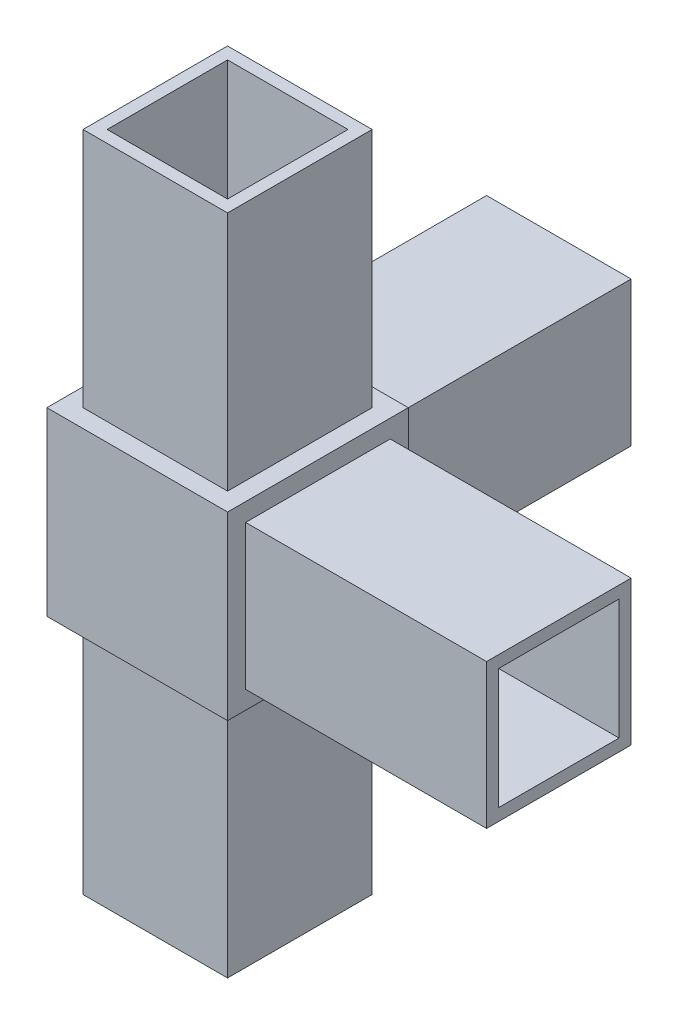
SolidWorks part; units mm, degrees
ref_plane "Alzado" through (0, 0, 0) normal (0, 0, 1) x (1, 0, 0)
ref_plane "Planta" through (0, 0, 0) normal (0, 1, 0) x (1, 0, 0)
ref_plane "Vista lateral" through (0, 0, 0) normal (1, 0, 0) x (0, 0, -1)
sketch "Croquis1" plane through (0, 0, 0) normal (0, 1, 0) x (1, 0, 0)
  line L1 (15, -15) -> (-15, -15)
  line L2 (15, -15) -> (15, 15)
  line L3 (15, 15) -> (-15, 15)
  line L4 (-15, -15) -> (-15, 15)
  line L5 (15, -15) -> (-15, 15) construction
  line L6 (15, 15) -> (-15, -15) construction
  line L7 (15, -15) -> (55, -15)
  line L8 (15, -15) -> (15, 15)
  line L9 (15, 15) -> (55, 15)
  line L10 (55, -15) -> (55, 15)
  line L11 (-15, 15) -> (15, 15)
  line L12 (-15, 15) -> (-15, 55)
  line L13 (-15, 55) -> (15, 55)
  line L14 (15, 15) -> (15, 55)
  point P0 (0, 0)
  dimension "D1" = 30
  dimension "D2" = 30
  dimension "D3" = 40
  dimension "D4" = 40
extrude "Extruir1" add sketch "Croquis1" along normal blind 30 contours L3 L14 L13 L12 | L4 L1 L2 L3 | L7 L10 L9 L2
sketch "Croquis5" plane through (0, 0, 0) normal (0, -1, 0) x (1, 0, 0)
  line L1 (-15, 15) -> (15, 15)
  line L2 (-15, 15) -> (-15, -15)
  line L3 (-15, -15) -> (15, -15)
  line L4 (15, 15) -> (15, -15)
extrude "Extruir4" add sketch "Croquis5" along normal blind 40
sketch "Croquis8" plane through (0, 30, 0) normal (0, 1, 0) x (1, 0, 0)
  line L1 (-15, -15) -> (15, -15)
  line L2 (-15, -15) -> (-15, 15)
  line L3 (-15, 15) -> (15, 15)
  line L4 (15, -15) -> (15, 15)
extrude "Extruir6" add sketch "Croquis8" along normal blind 40
sketch "Croquis9" plane through (0, 70, 0) normal (0, 1, 0) x (1, 0, 0)
  line L0 (-12, 12) -> (-12, -12)
  line L1 (-12, -12) -> (12, -12)
  line L2 (12, -12) -> (12, 12)
  line L3 (12, 12) -> (-12, 12)
  line L4 (-15, 15) -> (-15, -15)
  line L5 (-15, -15) -> (15, -15)
  line L6 (15, -15) -> (15, 15)
  line L7 (15, 15) -> (-15, 15)
  line L8 (-15, 15) -> (-15, -15)
  line L9 (-15, -15) -> (15, -15)
  line L10 (15, -15) -> (15, 15)
  line L11 (15, 15) -> (-15, 15)
  dimension "D1" = 0
  dimension "D2" = 3
extrude "Extruir7" cut sketch "Croquis9" against normal blind 40
sketch "Croquis2" plane through (55, 0, 0) normal (1, 0, 0) x (0, 0, -1)
  line L4 (-15, 0) -> (15, 0)
  line L5 (15, 0) -> (15, 30)
  line L6 (15, 30) -> (-15, 30)
  line L7 (-15, 30) -> (-15, 0)
  line L8 (-15, 0) -> (15, 0)
  line L9 (15, 0) -> (15, 30)
  line L10 (15, 30) -> (-15, 30)
  line L11 (-15, 30) -> (-15, 0)
  line L16 (-12, 3) -> (12, 3)
  line L17 (12, 3) -> (12, 27)
  line L18 (12, 27) -> (-12, 27)
  line L19 (-12, 27) -> (-12, 3)
  line L20 (-12, 3) -> (12, 3)
  line L21 (12, 3) -> (12, 27)
  line L22 (12, 27) -> (-12, 27)
  line L23 (-12, 27) -> (-12, 3)
  dimension "D1" = 0
  dimension "D2" = 3
extrude "Extruir2" cut sketch "Croquis2" against normal blind 40
sketch "Croquis3" plane through (0, 0, -55) normal (0, 0, -1) x (-1, 0, 0)
  line L0 (-12, 3) -> (12, 3)
  line L1 (12, 3) -> (12, 27)
  line L2 (12, 27) -> (-12, 27)
  line L3 (-12, 27) -> (-12, 3)
  line L4 (-15, 0) -> (15, 0)
  line L5 (15, 0) -> (15, 30)
  line L6 (15, 30) -> (-15, 30)
  line L7 (-15, 30) -> (-15, 0)
  line L8 (-15, 0) -> (15, 0)
  line L9 (15, 0) -> (15, 30)
  line L10 (15, 30) -> (-15, 30)
  line L11 (-15, 30) -> (-15, 0)
  dimension "D1" = 0
  dimension "D2" = 3
extrude "Extruir3" cut sketch "Croquis3" against normal blind 40
sketch "Croquis7" plane through (0, -40, 0) normal (0, -1, 0) x (1, 0, 0)
  line L0 (-12, 12) -> (-12, -12)
  line L1 (-12, -12) -> (12, -12)
  line L2 (12, -12) -> (12, 12)
  line L3 (12, 12) -> (-12, 12)
  line L4 (-15, 15) -> (-15, -15)
  line L5 (-15, -15) -> (15, -15)
  line L6 (15, -15) -> (15, 15)
  line L7 (15, 15) -> (-15, 15)
  line L8 (-15, 15) -> (-15, -15)
  line L9 (-15, -15) -> (15, -15)
  line L10 (15, -15) -> (15, 15)
  line L11 (15, 15) -> (-15, 15)
  dimension "D1" = 0
  dimension "D2" = 3
extrude "Extruir5" cut sketch "Croquis7" against normal blind 40
shell "Vaciado1" thickness 2
